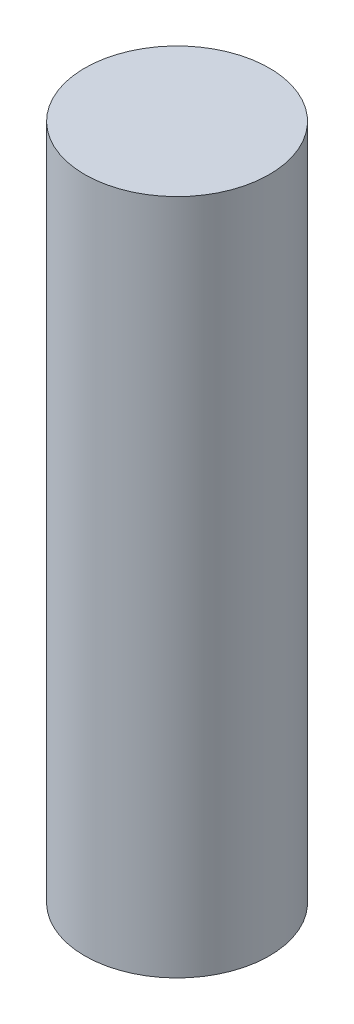
SolidWorks part; units mm, degrees
ref_plane "Alzado" through (0, 0, 0) normal (0, 0, 1) x (1, 0, 0)
ref_plane "Planta" through (0, 0, 0) normal (0, 1, 0) x (1, 0, 0)
ref_plane "Vista lateral" through (0, 0, 0) normal (1, 0, 0) x (0, 0, -1)
sketch "Croquis1" plane through (0, 0, 0) normal (0, 1, 0) x (1, 0, 0)
  circle A0 centre (0, 0) radius 1.5
  dimension "D1" = 3
extrude "Saliente-Extruir1" add sketch "Croquis1" along normal blind 11
